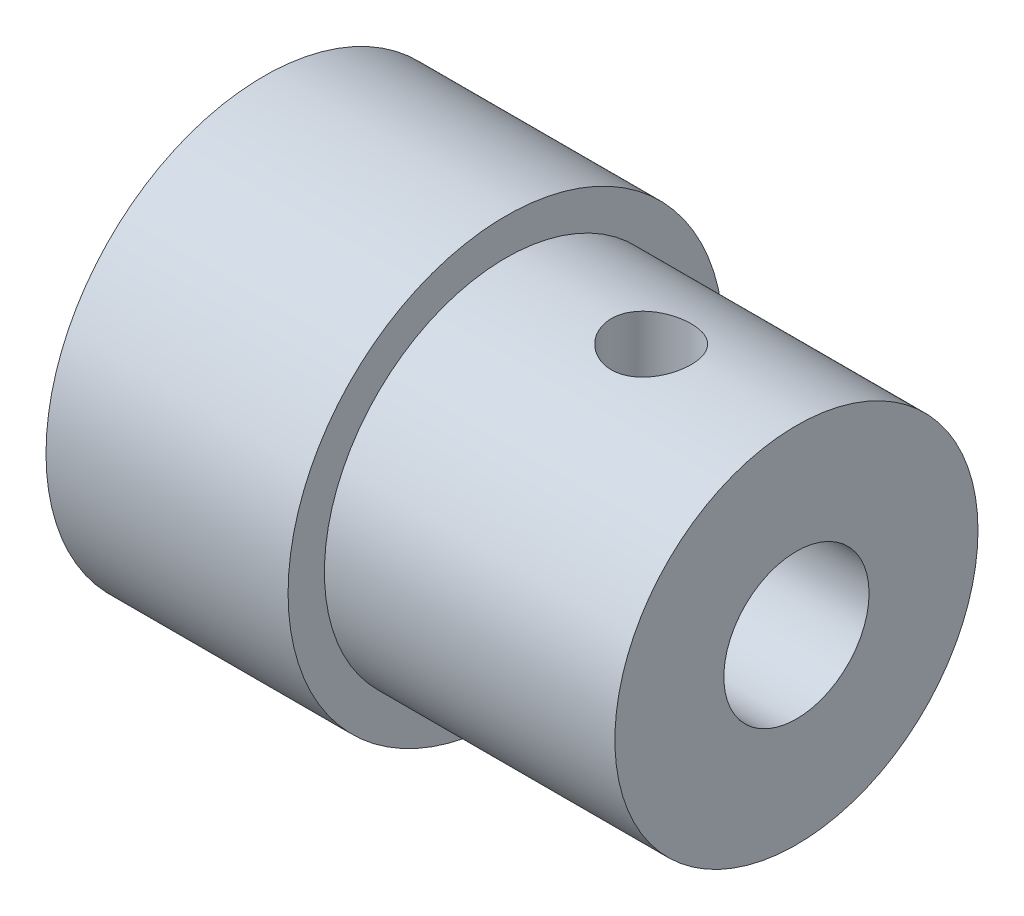
SolidWorks part; units mm, degrees
ref_plane "Plano frontal" through (0, 0, 0) normal (0, 0, 1) x (1, 0, 0)
ref_plane "Plano superior" through (0, 0, 0) normal (0, 1, 0) x (1, 0, 0)
ref_plane "Plano direito" through (0, 0, 0) normal (1, 0, 0) x (0, 0, -1)
sketch "Esboço1" plane through (0, 0, 0) normal (1, 0, 0) x (0, 0, -1)
  circle A0 centre (0, 0) radius 9
extrude "Ressalto-extrusão1" add sketch "Esboço1" along normal mid plane 22
sketch "Esboço2" plane through (11, 0, 0) normal (1, 0, 0) x (0, 0, -1)
  circle A0 centre (0, 0) radius 7.5
  circle A1 centre (0, 0) radius 9 construction
  circle A2 centre (0, 0) radius 9
extrude "Corte-extrusão1" cut sketch "Esboço2" against normal blind 12
sketch "Esboço3" plane through (11, 0, 0) normal (1, 0, 0) x (0, 0, -1)
  circle A0 centre (0, 0) radius 3
extrude "Corte-extrusão2" cut sketch "Esboço3" against normal blind 16
sketch "Esboço4" plane through (-11, 0, 0) normal (-1, 0, 0) x (0, 0, 1)
  circle A0 centre (0, 0) radius 2.1
extrude "Corte-extrusão3" cut sketch "Esboço4" against normal up to next
sketch "Esboço8" plane through (0, 0, 0) normal (0, 1, 0) x (1, 0, 0)
  line L0 (-1, 0) -> (11, 0)
  line L1 (-1, -9) -> (-1, 9) construction
  line L2 (11, -7.5) -> (11, 7.5) construction
  circle A0 centre (5, 0) radius 1.65
extrude "Corte-extrusão4" cut sketch "Esboço8" along normal through all contours A0
